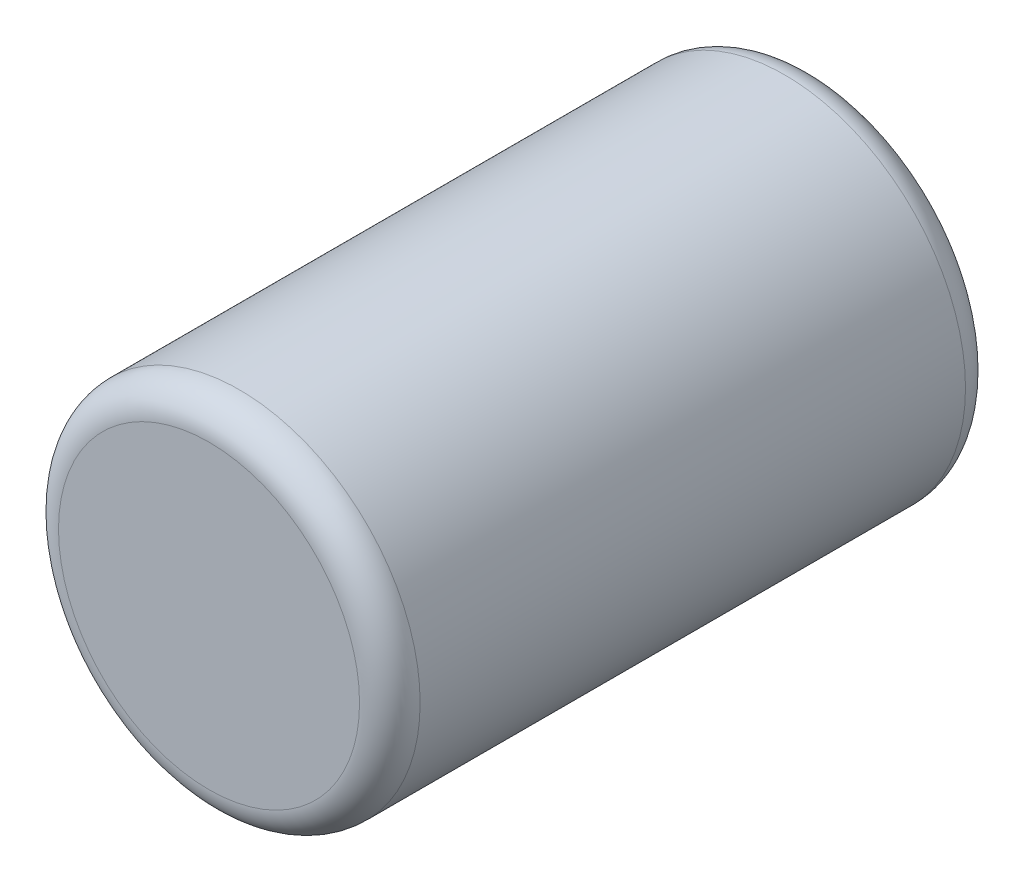
SolidWorks part; units mm, degrees
ref_plane "Front Plane" through (0, 0, 0) normal (0, 0, 1) x (1, 0, 0)
ref_plane "Top Plane" through (0, 0, 0) normal (0, 1, 0) x (1, 0, 0)
ref_plane "Right Plane" through (0, 0, 0) normal (1, 0, 0) x (0, 0, -1)
sketch "Sketch1" plane through (0, 0, 0) normal (0, 0, 1) x (1, 0, 0)
  circle A0 centre (0, 0) radius 37.8968
  dimension "D1" = 75.7936
extrude "Boss-Extrude1" add sketch "Sketch1" along normal blind 127
fillet "Fillet1" radius 6.35 2 edges at (37.8968, 0, 0) (37.8968, 0, 127)
